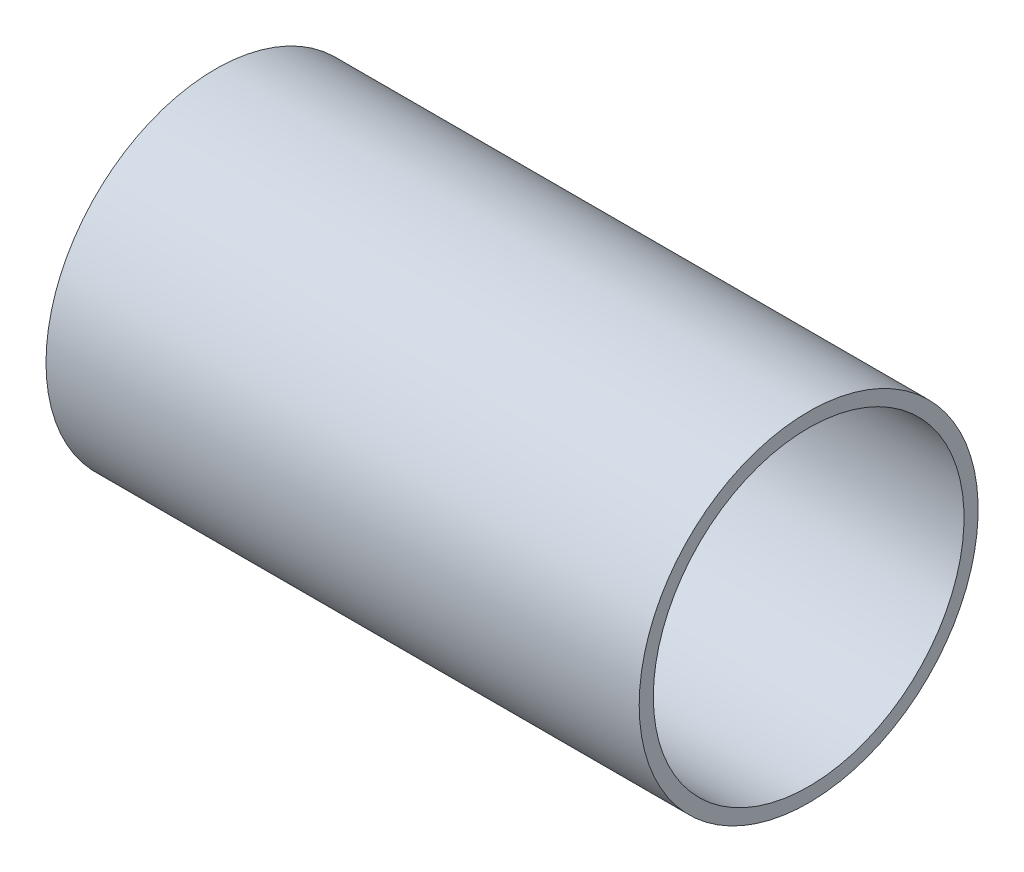
SolidWorks part; units mm, degrees
ref_plane "Front Plane" through (0, 0, 0) normal (0, 0, 1) x (1, 0, 0)
ref_plane "Top Plane" through (0, 0, 0) normal (0, 1, 0) x (1, 0, 0)
ref_plane "Right Plane" through (0, 0, 0) normal (1, 0, 0) x (0, 0, -1)
sketch "Sketch1" plane through (0, 0, 0) normal (0, 0, 1) x (1, 0, 0)
  line L0 (0, 0) -> (24.5122, 0) construction
  line L1 (0, 12) -> (42, 12)
  line L2 (42, 12) -> (42, 11)
  line L3 (42, 11) -> (0, 11)
  line L4 (0, 11) -> (0, 12)
  dimension "D1" = 24
  dimension "D2" = 22
  dimension "D3" = 42
revolve "Revolve1" add sketch "Sketch1" angle 360 about L0
